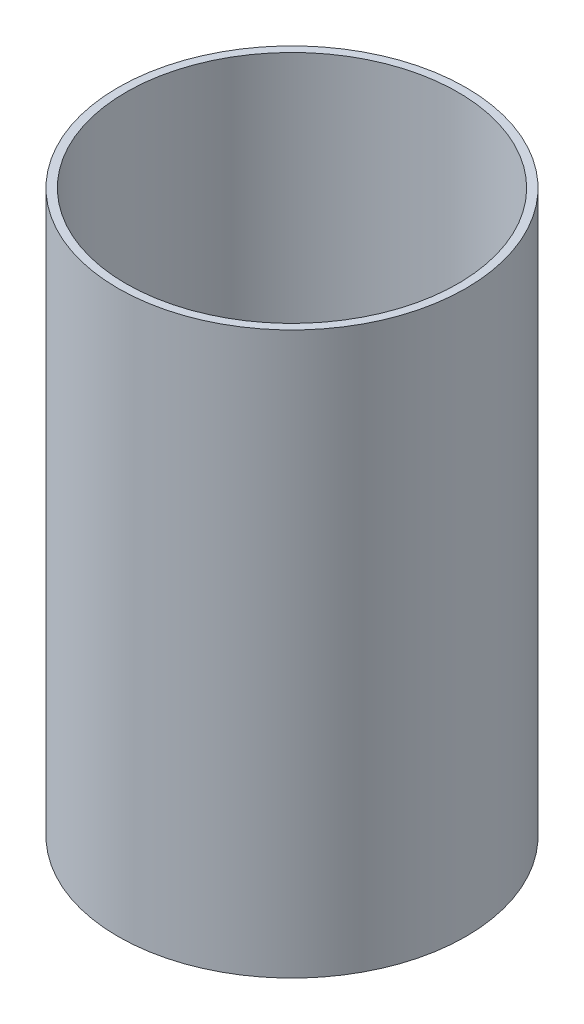
SolidWorks part; units mm, degrees
ref_plane "Front Plane" through (0, 0, 0) normal (0, 0, 1) x (1, 0, 0)
ref_plane "Top Plane" through (0, 0, 0) normal (0, 1, 0) x (1, 0, 0)
ref_plane "Right Plane" through (0, 0, 0) normal (1, 0, 0) x (0, 0, -1)
sketch "Sketch1" plane through (0, 0, 0) normal (0, 1, 0) x (1, 0, 0)
  circle A0 centre (0, 0) radius 109.9312
  circle A1 centre (0, 0) radius 104.8512
  dimension "D1" = 219.8624
  dimension "D2" = 209.7024
extrude "Boss-Extrude1" add sketch "Sketch1" along normal blind 354.6856
